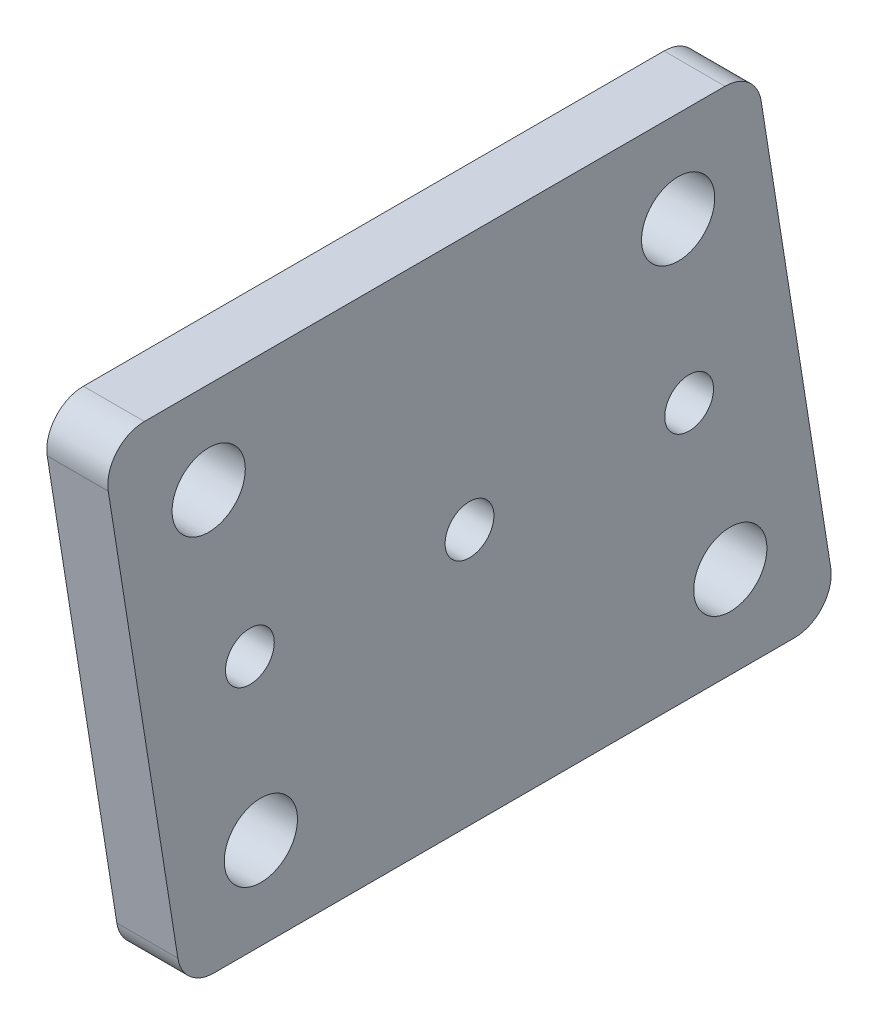
SolidWorks part; units mm, degrees
ref_plane "Front Plane" through (0, 0, 0) normal (0, 0, 1) x (1, 0, 0)
ref_plane "Top Plane" through (0, 0, 0) normal (0, 1, 0) x (1, 0, 0)
ref_plane "Right Plane" through (0, 0, 0) normal (1, 0, 0) x (0, 0, -1)
sketch "Sketch1" plane through (0, 0, 0) normal (1, 0, 0) x (0, 0, -1)
  line L0 (-0.6067, 45.3815) -> (9.9652, -21.3667) construction
  line L1 (-0.6067, 45.3815) -> (24.7049, 45.3815) construction
  line L2 (24.7049, 45.3815) -> (35.2768, -21.3667) construction
  line L3 (35.2768, -21.3667) -> (9.9652, -21.3667) construction
  line L4 (0, 0) -> (38.4737, 0) construction
  line L5 (0, 0) -> (-4.2764, 27) construction
  line L6 (38.4737, 0) -> (34.1973, 27) construction
  line L7 (-4.2764, 27) -> (34.1973, 27) construction
  line L8 (-2.1382, 13.5) -> (36.3355, 13.5) construction
  line L9 (-2.9301, 18.5) -> (35.5436, 18.5) construction
  line L10 (-1.3463, 8.5) -> (37.1274, 8.5) construction
  line L11 (-6.4056, -7.5) -> (47.255, -7.5)
  line L12 (47.255, -7.5) -> (40.6029, 34.5)
  line L13 (40.6029, 34.5) -> (-13.0578, 34.5)
  line L14 (-13.0578, 34.5) -> (-6.4056, -7.5)
  circle A0 centre (0, 0) radius 6.5 construction
  circle A1 centre (0, 0) radius 7.5 construction
  circle A2 centre (0, 0) radius 3
  circle A3 centre (38.4737, 0) radius 3
  circle A4 centre (38.4737, 0) radius 6.5 construction
  circle A5 centre (38.4737, 0) radius 7.5 construction
  circle A6 centre (-4.2764, 27) radius 3
  circle A7 centre (-4.2764, 27) radius 6.5 construction
  circle A8 centre (-4.2764, 27) radius 7.5 construction
  circle A9 centre (34.1973, 27) radius 3
  circle A10 centre (34.1973, 27) radius 6.5 construction
  circle A11 centre (34.1973, 27) radius 7.5 construction
  circle A12 centre (17.0986, 13.5) radius 2
  circle A13 centre (-0.9014, 13.5) radius 2
  circle A14 centre (35.0986, 13.5) radius 2
  dimension "D1" = 15
  dimension "D2" = 13
  dimension "D3" = 6
  dimension "D9" = 18
  dimension "D10" = 18
  dimension "D11" = 4
  dimension "D4" = 99
  dimension "D5" = 25
  dimension "D6" = 27
  dimension "D7" = 5
  dimension "D8" = 5
  dimension "D12" = 42
extrude "Boss-Extrude1" add sketch "Sketch1" along normal blind 5
fillet "Fillet1" radius 3 4 edges at (2.5, 34.5, -40.6029) (2.5, -7.5, -47.255) (2.5, -7.5, 6.4056) (2.5, 34.5, 13.0578)
